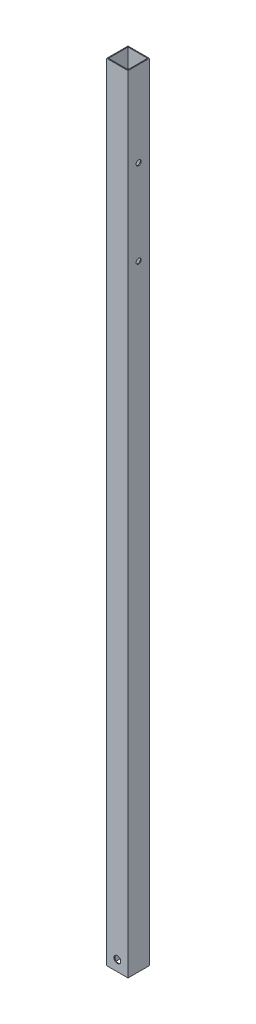
SolidWorks part; units mm, degrees
ref_plane "Front Plane" through (0, 0, 0) normal (0, 0, 1) x (1, 0, 0)
ref_plane "Top Plane" through (0, 0, 0) normal (0, 1, 0) x (1, 0, 0)
ref_plane "Right Plane" through (0, 0, 0) normal (1, 0, 0) x (0, 0, -1)
sketch "Sketch1" plane through (0, 0, 0) normal (0, 1, 0) x (1, 0, 0)
  line L0 (-11.5, -11.5) -> (11.5, -11.5)
  line L1 (-12.5, -12.5) -> (12.5, -12.5)
  line L2 (-12.5, -12.5) -> (-12.5, 12.5)
  line L3 (-12.5, 12.5) -> (12.5, 12.5)
  line L4 (12.5, -12.5) -> (12.5, 12.5)
  line L5 (-12.5, -12.5) -> (12.5, 12.5) construction
  line L6 (-12.5, 12.5) -> (12.5, -12.5) construction
  line L7 (11.5, -11.5) -> (11.5, 11.5)
  line L8 (-11.5, 11.5) -> (11.5, 11.5)
  line L9 (-11.5, -11.5) -> (-11.5, 11.5)
  point P0 (0, 0)
  dimension "D2" = 25
  dimension "D1" = 1
extrude "Boss-Extrude1" add sketch "Sketch1" along normal blind 922.5
sketch "Sketch2" plane through (12.5, 0, 0) normal (1, 0, 0) x (0, 0, -1)
  line L0 (0, 0) -> (0, 922.5) construction
  line L1 (-12.5, 922.5) -> (12.5, 922.5) construction
  circle A0 centre (0, 822.5) radius 3
  circle A1 centre (0, 722.5) radius 3
  dimension "D1" = 100
  dimension "D3" = 6
  dimension "D2" = 100
extrude "Cut-Extrude1" cut sketch "Sketch2" against normal through all
sketch "Sketch3" plane through (0, 0, 12.5) normal (0, 0, 1) x (1, 0, 0)
  line L0 (-12.5, 0) -> (12.5, 0) construction
  line L1 (12.5, 922.5) -> (12.5, 0) construction
  circle A0 centre (0, 12.5) radius 4
  dimension "D1" = 12.5
  dimension "D2" = 12.5
  dimension "D3" = 8
extrude "Cut-Extrude2" cut sketch "Sketch3" against normal through all
